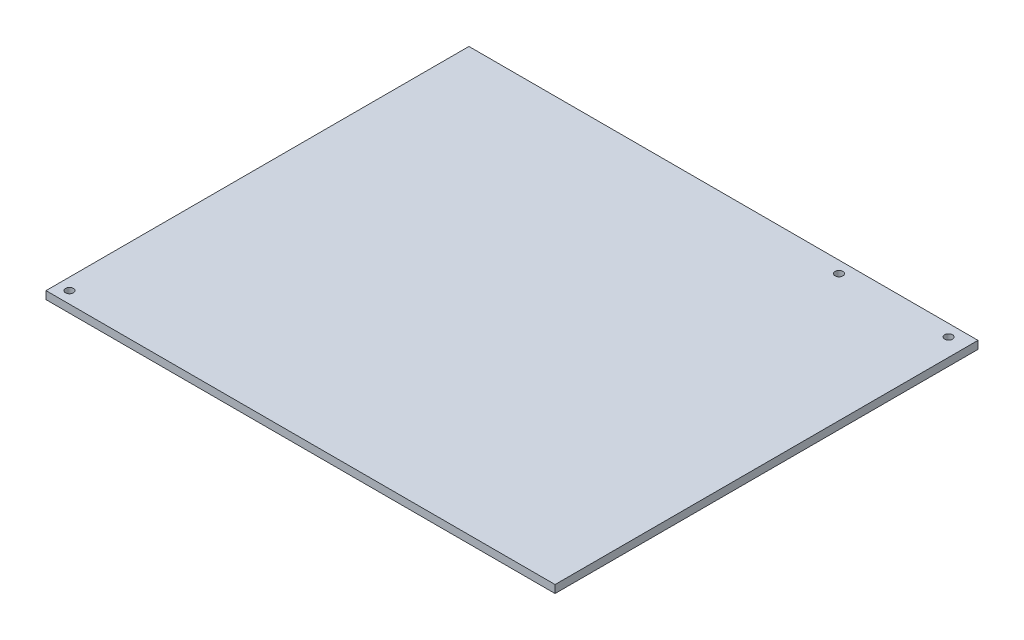
SolidWorks part; units mm, degrees
ref_plane "Front Plane" through (0, 0, 0) normal (0, 0, 1) x (1, 0, 0)
ref_plane "Top Plane" through (0, 0, 0) normal (0, 1, 0) x (1, 0, 0)
ref_plane "Right Plane" through (0, 0, 0) normal (1, 0, 0) x (0, 0, -1)
sketch "Sketch1" plane through (0, 0, 0) normal (0, 1, 0) x (1, 0, 0)
  line L0 (3, 0) -> (3, 3) construction
  line L1 (0, 0) -> (130, 0)
  line L2 (0, 0) -> (0, 108)
  line L3 (0, 108) -> (130, 108)
  line L4 (130, 0) -> (130, 108)
  line L5 (125.5, 108) -> (125.5, 105) construction
  line L6 (125.5, 105) -> (97.5, 105) construction
  circle A0 centre (3, 3) radius 1
  circle A1 centre (125.5, 105) radius 1
  circle A2 centre (97.5, 105) radius 1
  point P7 (3, 1.5)
  point P11 (125.5, 106.5)
  dimension "D5" = 2
  dimension "D8" = 2
  dimension "D10" = 2
  dimension "D1" = 130
  dimension "D2" = 108
  dimension "D3" = 3
  dimension "D4" = 3
  dimension "D6" = 3
  dimension "D7" = 4.5
  dimension "D9" = 28
extrude "Boss-Extrude1" add sketch "Sketch1" along normal blind 2
